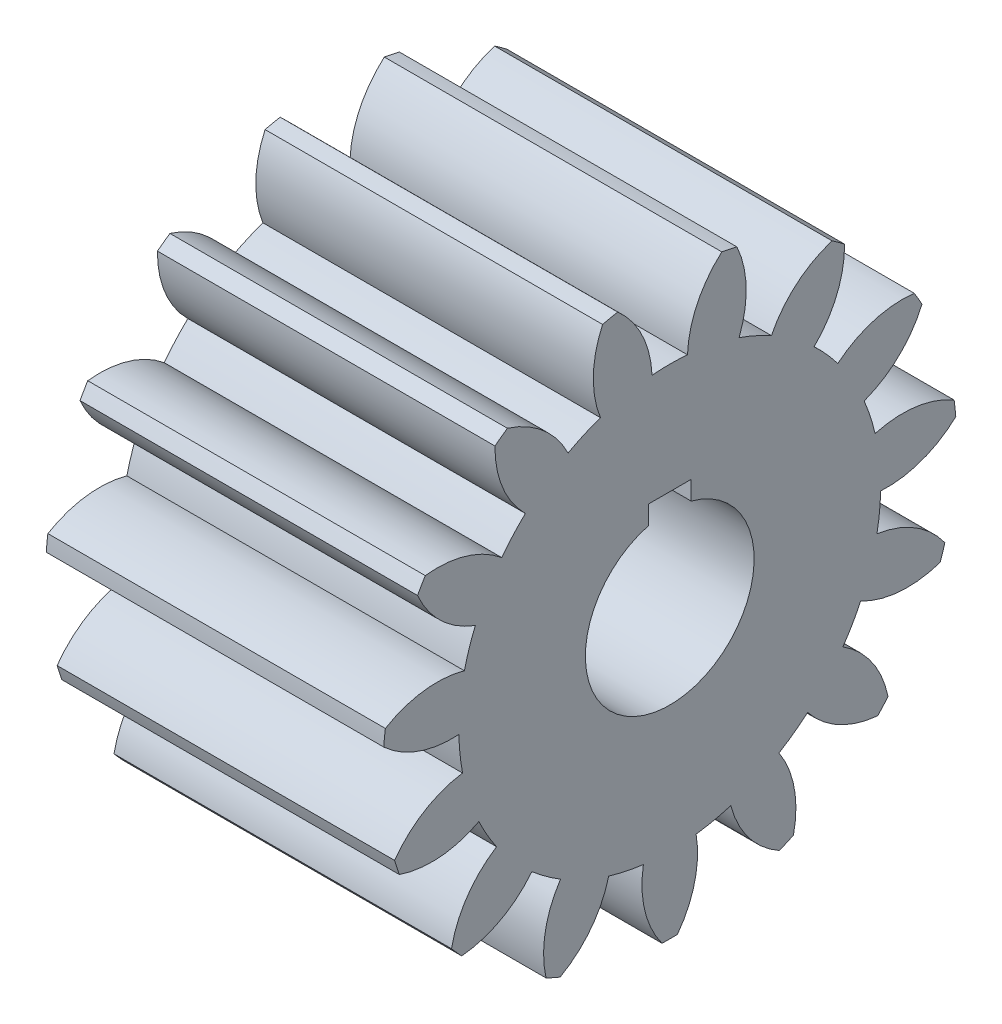
SolidWorks part; units mm, degrees
ref_plane "Plane1" through (0, 0, 0) normal (0, 0, 1) x (1, 0, 0)
ref_plane "Plane2" through (0, 0, 0) normal (0, 1, 0) x (1, 0, 0)
ref_plane "Plane3" through (0, 0, 0) normal (1, 0, 0) x (0, 0, -1)
sketch "HoldingSke" plane through (0, 0, 0) normal (0, 1, 0) x (1, 0, 0)
  line L0 (0, 0) -> (0.1932, -0.0518)
  line L1 (-15, 0) -> (100, 0) construction
  line L2 (0, 0) -> (-2.1039, 2.3779)
  line L3 (0, 0) -> (-11.863, 4.5341)
  line L4 (0, 0) -> (8.3417, 2.2352)
  line L5 (0, 0) -> (-46.8476, -17.4728)
  line L6 (0, 0) -> (-41.4481, -27.9652)
  line L7 (-2.1039, 2.3779) -> (8.6586, 51.2059)
  line L8 (-76.2, 54.61) -> (-72.9, 54.61)
  line L9 (-71.009, 38.7566) -> (-53.1078, 45.2721)
  line L10 (-76.2, 71.12) -> (104.1128, 71.12)
  line L11 (0, 0) -> (-50, 0)
  line L12 (-76.2, 101.6) -> (-76.033, 101.6)
  line L13 (24.9733, 27.94) -> (52.9518, 28.4284)
  line L14 (24.9733, 27.94) -> (24.9743, 27.94)
  line L15 (24.9733, 27.94) -> (100.4006, 29.5858)
  line L16 (-63.627, -5) -> (-12.827, -5)
  circle A0 centre (0, 0) radius 12.5
  circle A1 centre (0, 0) radius 31.249
  circle A2 centre (0, 0) radius 37.5
  circle A3 centre (0, 0) radius 12.5
  dimension "MHD" = 62.498
  dimension "Hub_dia" = 75
  dimension "Bore" = 25
  dimension "MBD" = 25
  dimension "Num_teeth" = 15
  dimension "Pitch_radius" = 180.3128
  dimension "Pitch" = 0.2
  dimension "Width" = 50
  dimension "Overall_len" = 50
  dimension "Show_teeth" = 15
  dimension "Thickness" = 50
  dimension "OAL" = 50.0001
  dimension "T_dim" = 3.3
  dimension "Ap" = 20
  dimension "H" = 19.05
  dimension "Backlash" = 0.167
  dimension "Addendum_fac" = 1
  dimension "Dedendum_fac" = 1.25
  dimension "Clearance_fac" = 0.25
  dimension "Dedendum_add" = 0.001
  dimension "Module" = 5
sketch "BasProSke" plane through (0, 0, 0) normal (0, 1, 0) x (1, 0, 0)
  line L0 (-10, 0) -> (60, 0) construction
  line L1 (0, 0) -> (0, 42.5)
  line L2 (0, 0) -> (50, 0)
  line L3 (50, 0) -> (50, 42.5)
  line L4 (50, 42.5) -> (0, 42.5)
  dimension "Diameter" = 85
  dimension "Thickness" = 50
revolve "Base-Revolve" add sketch "BasProSke" angle 360 about L0
sketch "TooCutSke" plane through (0, 0, 0) normal (1, 0, 0) x (0, 0, -1)
  line L1 (0, 0) -> (0, 107) construction
  line L2 (0, 0) -> (-4.2118, 37.2627) construction
  line L3 (0, 0) -> (-15.5202, 73.017) construction
  line L4 (-4.2118, 37.2627) -> (-7.7601, 36.5085) construction
  arc A0 (2.6245, 31.1386) -> (-2.6245, 31.1386) centre (0, 0) ccw
  arc A1 (7.7397, 41.8152) -> (-7.7397, 41.8152) centre (0, 0) ccw
  circle A2 centre (0, 0) radius 37.5 construction
  circle A3 centre (0, 0) radius 35.2385 construction
  arc A4 (-2.6245, 31.1386) -> (-7.7397, 41.8152) centre (-17.6118, 30.5217) ccw
  arc A5 (7.7397, 41.8152) -> (2.6245, 31.1386) centre (17.6118, 30.5217) ccw
  dimension "Root_dia" = 62.498
  dimension "Overcut_dia" = 85.0508
  dimension "Pitch_dia" = 75
  dimension "Base_dia" = 70.4769
  dimension "Flank_rad" = 15
  dimension "Half_ang" = 12
  dimension "Half_CT" = 3.6276
extrude "ToothCut" cut sketch "TooCutSke" along normal through all
fillet "Breaks" [suppressed] radius 0.1
fillet "RootFillets" [suppressed] radius 1.251
pattern_circular "TeethCuts" count 15 every 24 about axis through (-10, 0, 0) along (1, 0, 0) of "ToothCut", "RootFillets", "Breaks"
sketch "HubNeaOneSke" plane through (0, 0, 0) normal (-1, 0, 0) x (0, 0, 1)
  circle A0 centre (0, 0) radius 31.249
  dimension "Diameter" = 62.498
extrude "HubNearOne" [suppressed] add sketch "HubNeaOneSke" along normal blind 12.7001
sketch "HubNeaBotSke" plane through (0, 0, 0) normal (-1, 0, 0) x (0, 0, 1)
  circle A0 centre (0, 0) radius 31.249
  dimension "Diameter" = 62.498
extrude "HubNearBoth" [suppressed] add sketch "HubNeaBotSke" along normal blind 6.35
ref_plane "FarPln" through (50, 0, 0) normal (1, 0, 0) x (0, 0, -1)
sketch "HubFarSke" plane through (50, 0, 0) normal (1, 0, 0) x (0, 0, -1)
  circle A0 centre (0, 0) radius 31.249
  dimension "Diameter" = 62.498
extrude "HubFar" [suppressed] add sketch "HubFarSke" along normal blind 6.35
sketch "BorSke" plane through (0, 0, 0) normal (1, 0, 0) x (0, 0, -1)
  circle A0 centre (0, 0) radius 12.5
  dimension "Diameter" = 25
extrude "Bore" cut sketch "BorSke" along normal mid plane 100.0001
sketch "KeySke" plane through (0, 0, 0) normal (1, 0, 0) x (0, 0, -1)
  line L0 (-3.175, 0) -> (-3.175, 14.8812)
  line L1 (-3.175, 14.8812) -> (3.175, 14.8812)
  line L2 (3.175, 14.8812) -> (3.175, 0)
  line L3 (0, 0) -> (0, 34) construction
  line L4 (-3.175, 0) -> (3.175, 0)
  dimension "Offset" = 14.8812
  dimension "Width" = 6.35
extrude "Keyway" cut sketch "KeySke" along normal mid plane 100.0001
pattern_circular "Keyway2" [suppressed] count 2 every 90 about axis through (-10, 0, 0) along (1, 0, 0)
equation "' \"Module@HoldingSke\" = 6.35"
equation "' \"Num_teeth@HoldingSke\" = 12"
equation "' \"Ap@HoldingSke\" =  20"
equation "' \"Width@HoldingSke\" = 0.5 * 25.4"
equation "' \"Hub_dia@HoldingSke\"= 1 * 25.4"
equation "' \"Overall_len@HoldingSke\" = 1.0 * 25.4"
equation "' \"Bore@HoldingSke\" = 0.75 * 25.4"
equation "' \"T_dim@HoldingSke\" = 0.1 * 25.4"
equation "' \"Width@KeySke\" = 0.25 * 25.4"
equation "' \"Show_teeth@HoldingSke\" = 13"
equation "' \"Backlash@HoldingSke\" = 0.009 * 25.4"
equation "' \"Addendum_fac@HoldingSke\" = 1.0"
equation "' \"Dedendum_fac@HoldingSke\" = 1.25"
equation "' \"Dedendum_add@HoldingSke\" = 0.00005 * 25.4"
equation "' \"Clearance_fac@HoldingSke\" = 0.25"
equation "\"Pitch@HoldingSke\" = 1 / \"Module@HoldingSke\""
equation "\"Overcut_dia@TooCutSke\" = (\"Num_teeth@HoldingSke\" + 2 * \"Addendum_fac@HoldingSke\") / \"Pitch@HoldingSke\" + 0.002 * 25.4"
equation "\"Pitch_dia@TooCutSke\" = \"Num_teeth@HoldingSke\" / \"Pitch@HoldingSke\""
equation "\"Base_dia@TooCutSke\" = \"Num_teeth@HoldingSke\" / \"Pitch@HoldingSke\" * cos((\"Ap@HoldingSke\"  * 3.14159265 / 180))"
equation "\"Root_dia@TooCutSke\" = (\"Num_teeth@HoldingSke\" + 2) / \"Pitch@HoldingSke\" - 2 * (\"Addendum_fac@HoldingSke\" + \"Dedendum_fac@HoldingSke\") / \"Pitch@HoldingSke\" - \"Dedendum_add@HoldingSke\" * 2"
equation "\"Half_ang@TooCutSke\" = 180 / \"Num_teeth@HoldingSke\""
equation "\"Half_CT@TooCutSke\" = \"Num_teeth@HoldingSke\" / \"Pitch@HoldingSke\" * sin((3.14159265 / 2 / \"Num_teeth@HoldingSke\")) / 2 - 7 * \"Backlash@HoldingSke\" / 4"
equation "\"Flank_rad@TooCutSke\" = \"Num_teeth@HoldingSke\" / \"Pitch@HoldingSke\" / 5"
equation "\"Radius@RootFillets\" = \"Clearance_fac@HoldingSke\" / \"Pitch@HoldingSke\" + \"Dedendum_add@HoldingSke\""
equation "\"Break_rad@Breaks\" = 0.02 / \"Pitch@HoldingSke\""
equation "\"Thickness@HoldingSke\" = \"Width@HoldingSke\""
equation "\"OAL@HoldingSke\" = \"Thickness@HoldingSke\""
equation "\"MHD@HoldingSke\" = (\"Num_teeth@HoldingSke\" + 2) / \"Pitch@HoldingSke\" - 2 * (\"Addendum_fac@HoldingSke\" + \"Dedendum_fac@HoldingSke\")  / \"Pitch@HoldingSke\" - \"Dedendum_add@HoldingSke\" * 2"
equation "\"MBD@HoldingSke\" = (\"Num_teeth@HoldingSke\" + 2) / \"Pitch@HoldingSke\" - 2 * (\"Addendum_fac@HoldingSke\" + \"Dedendum_fac@HoldingSke\")  / \"Pitch@HoldingSke\" - \"Dedendum_add@HoldingSke\" * 2 - 0.002 * 25.4"
equation "\"MHD@HoldingSke\" = ((sgn( \"MHD@HoldingSke\" - \"Hub_dia@HoldingSke\" )-1)*( \"MHD@HoldingSke\" - \"Hub_dia@HoldingSke\" ))/-2+ \"Hub_dia@HoldingSke\""
equation "\"MBD@HoldingSke\" = ((sgn( \"MBD@HoldingSke\" - \"Bore@HoldingSke\" )-1)*( \"MBD@HoldingSke\" - \"Bore@HoldingSke\" ))/-2+ \"Bore@HoldingSke\""
equation "\"OAL@HoldingSke\" = ((sgn( \"OAL@HoldingSke\" - \"Overall_len@HoldingSke\" )+1)*( \"OAL@HoldingSke\" - \"Overall_len@HoldingSke\" ))/2 + \"Overall_len@HoldingSke\" + 0.000002 * 25.4"
equation "\"Num_teeth@TeethCuts\" = int( \"Show_teeth@HoldingSke\" ) + 1"
equation "\"Num_teeth@TeethCuts\" = ((sgn( \"Num_teeth@TeethCuts\" - \"Num_teeth@HoldingSke\" )-1)*( \"Num_teeth@TeethCuts\" - \"Num_teeth@HoldingSke\" ))/-2+ \"Num_teeth@HoldingSke\""
equation "\"Num_teeth@TeethCuts\" = ((sgn( \"Num_teeth@TeethCuts\" - 2.0)+1)*( \"Num_teeth@TeethCuts\" - 2.0))/2 +2.0"
equation "\"Angle@TeethCuts\" = 360.0 / \"Num_teeth@HoldingSke\""
equation "\"Diameter@BasProSke\" = (\"Num_teeth@HoldingSke\" + 2 * \"Addendum_fac@HoldingSke\") / \"Pitch@HoldingSke\""
equation "\"Thickness@BasProSke\"  = \"Thickness@HoldingSke\""
equation "' \"Fillet_rad@BasProSke\" =  \"Thickness@HoldingSke\" * 0.05"
equation "\"MHD@HoldingSke\" = ((sgn( \"MHD@HoldingSke\" - \"Root_dia@TooCutSke\" )-1)*( \"MHD@HoldingSke\" - \"Root_dia@TooCutSke\" ))/-2+ \"Root_dia@TooCutSke\""
equation "\"Diameter@HubNeaOneSke\" = \"MHD@HoldingSke\""
equation "\"Length@HubNearOne\" = \"OAL@HoldingSke\" - \"Thickness@BasProSke\""
equation "\"Diameter@HubNeaBotSke\" = \"MHD@HoldingSke\""
equation "\"Length@HubNearBoth\" = ( \"OAL@HoldingSke\" - \"Thickness@BasProSke\" ) / 2.0"
equation "\"Thickness@FarPln\" = \"Thickness@BasProSke\""
equation "\"Diameter@HubFarSke\" = \"MHD@HoldingSke\""
equation "\"Length@HubFar\" = ( \"OAL@HoldingSke\" - \"Thickness@BasProSke\" ) / 2.0"
equation "\"Diameter@BorSke\" = \"MBD@HoldingSke\""
equation "\"D1@Bore\" = \"OAL@HoldingSke\" * 2.0"
equation "\"D1@Keyway\" = \"OAL@HoldingSke\" * 2.0"
